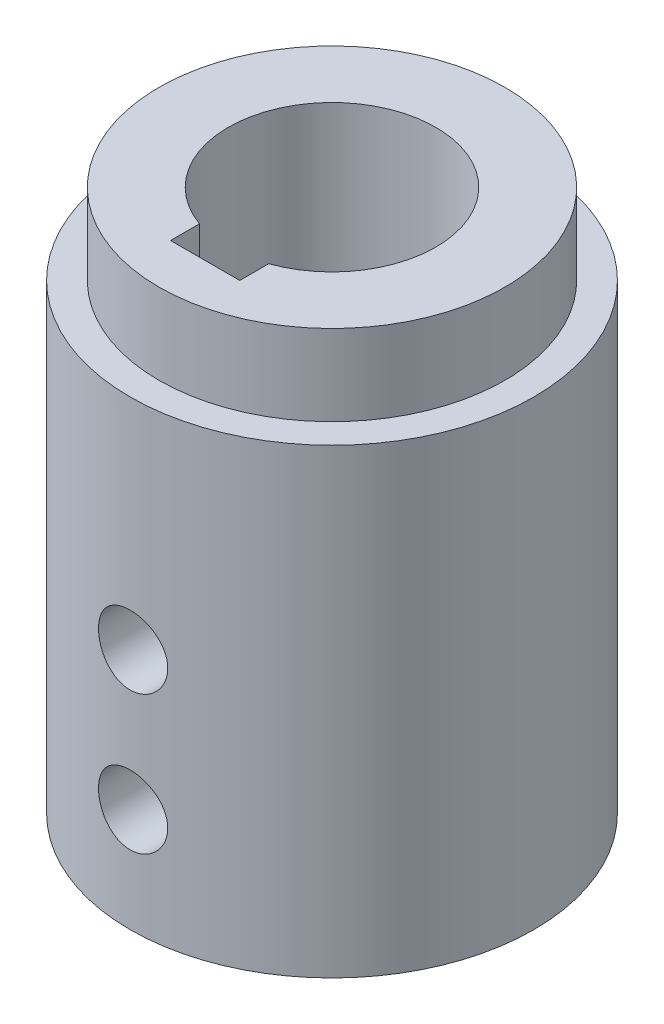
SolidWorks part; units mm, degrees
material "Cast Carbon Steel"
ref_plane "Front Plane" through (0, 0, 0) normal (0, 0, 1) x (1, 0, 0)
ref_plane "Top Plane" through (0, 0, 0) normal (0, 1, 0) x (1, 0, 0)
ref_plane "Right Plane" through (0, 0, 0) normal (1, 0, 0) x (0, 0, -1)
sketch "Sketch1" plane through (0, 0, 0) normal (0, 1, 0) x (1, 0, 0)
  circle A0 centre (0, 0) radius 17.5
extrude "Boss-Extrude1" add sketch "Sketch1" along normal blind 47
sketch "Sketch2" plane through (0, 47, 0) normal (0, 1, 0) x (1, 0, 0)
  circle A0 centre (0, 0) radius 17.5
  circle A1 centre (0, 0) radius 15
extrude "Cut-Extrude1" cut sketch "Sketch2" against normal blind 7
sketch "Sketch3" plane through (0, 0, 0) normal (0, -1, 0) x (1, 0, 0)
  line L1 (0, 11) -> (-3, 11)
  line L2 (0, 11) -> (3, 11)
  line L3 (-3, 11) -> (-3, 8.4853)
  line L4 (3, 11) -> (3, 8.4853)
  arc A0 (-3, 8.4853) -> (3, 8.4853) centre (0, 0) ccw
extrude "Cut-Extrude2" cut sketch "Sketch3" against normal through all
sketch "Sketch4" plane through (0, 0, 11) normal (0, 0, -1) x (-1, 0, 0)
  line L0 (-3, 0) -> (3, 0) construction
  circle A0 centre (0, 9) radius 3
  circle A1 centre (0, 21) radius 3
  dimension "D1" = 6
  dimension "D2" = 6
  dimension "D3" = 9
  dimension "D4" = 21
extrude "Cut-Extrude3" cut sketch "Sketch4" against normal up to surface (6.2409 mm away)
